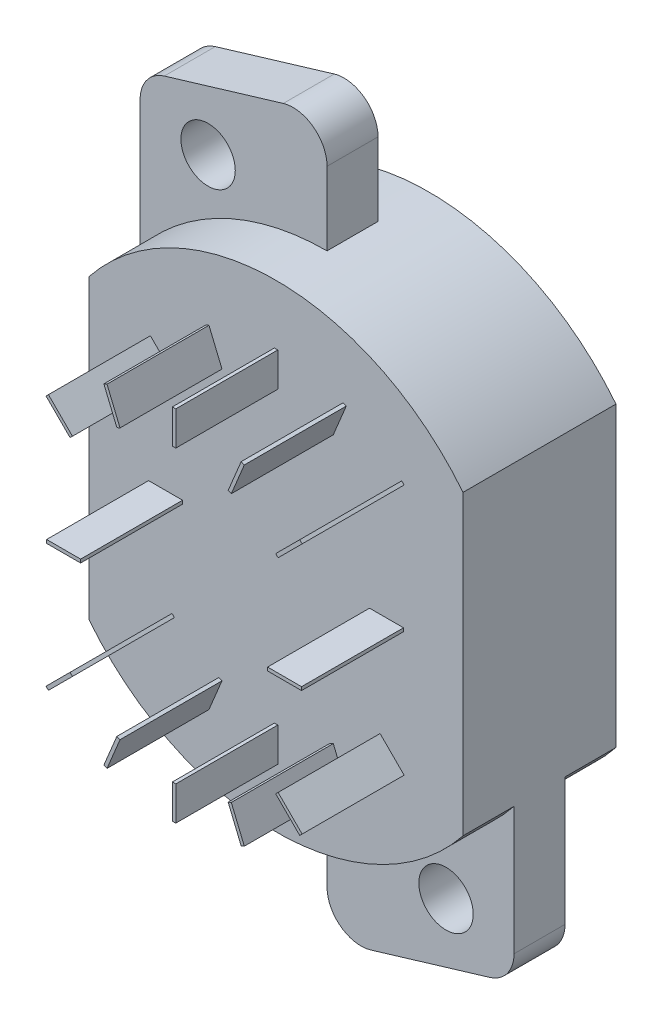
SolidWorks part; units mm, degrees
ref_plane "正面" through (0, 0, 0) normal (0, 0, 1) x (1, 0, 0)
ref_plane "平面" through (0, 0, 0) normal (0, 1, 0) x (1, 0, 0)
ref_plane "右側面" through (0, 0, 0) normal (1, 0, 0) x (0, 0, -1)
sketch "ｽｹｯﾁ1" plane through (0, 0, 0) normal (0, 0, 1) x (1, 0, 0)
  line L1 (-11, 8.75) -> (11, 8.75) construction
  line L2 (-11, 8.75) -> (-11, -8.75)
  line L3 (-11, -8.75) -> (11, -8.75) construction
  line L4 (11, 8.75) -> (11, -8.75)
  line L5 (-11, 8.75) -> (11, -8.75) construction
  line L6 (-11, -8.75) -> (11, 8.75) construction
  arc A0 (-11, 8.75) -> (11, 8.75) centre (0, 0) cw
  arc A1 (-11, -8.75) -> (11, -8.75) centre (0, 0) ccw
  point P0 (0, 0)
  dimension "D1" = 17.5
  dimension "D2" = 22
extrude "ﾎﾞｽ - 押し出し1" add sketch "ｽｹｯﾁ1" along normal blind 3
sketch "ｽｹｯﾁ2" plane through (0, 0, 3) normal (0, 0, 1) x (1, 0, 0)
  line L0 (-11, 8.75) -> (-11, 17.75)
  line L1 (-11, 17.75) -> (0, 21.0557)
  line L2 (0, 21.0557) -> (0, 14.0557)
  line L3 (11, -8.75) -> (11, -17.75)
  line L4 (11, -17.75) -> (0, -21.0557)
  line L5 (0, -21.0557) -> (0, -14.0557)
  line L8 (11, -8.75) -> (11, 8.75)
  line L9 (-11, 8.75) -> (-11, -8.75)
  line L10 (11, -8.75) -> (11, 8.75)
  line L11 (-11, 8.75) -> (-11, -8.75)
  arc A0 (11, 8.75) -> (-11, 8.75) centre (0, 0) ccw construction
  arc A1 (-11, -8.75) -> (11, -8.75) centre (0, 0) ccw construction
  arc A2 (0, -14.0557) -> (11, -8.75) centre (0, 0) ccw construction
  arc A3 (0, 14.0557) -> (-11, 8.75) centre (0, 0) ccw construction
  arc A4 (11, 8.75) -> (0, 14.0557) centre (0, 0) ccw construction
  arc A5 (-11, -8.75) -> (0, -14.0557) centre (0, 0) ccw construction
  arc A6 (0, -14.0557) -> (11, -8.75) centre (0, 0) ccw construction
  arc A7 (0, 14.0557) -> (-11, 8.75) centre (0, 0) ccw construction
  arc A8 (-11, -8.75) -> (11, -8.75) centre (0, 0) ccw
  arc A9 (11, 8.75) -> (-11, 8.75) centre (0, 0) ccw
  arc A10 (-11, -8.75) -> (0, -14.0557) centre (0, 0) ccw
  arc A11 (11, 8.75) -> (0, 14.0557) centre (0, 0) ccw
  dimension "D1" = 7
  dimension "D2" = 9
  dimension "D3" = 9
  dimension "D4" = 7
  dimension "D5" = 0
extrude "ﾎﾞｽ - 押し出し2" add sketch "ｽｹｯﾁ2" along normal blind 3
sketch "ｽｹｯﾁ3" plane through (0, 0, 6) normal (0, 0, 1) x (1, 0, 0)
  line L1 (-11, 8.75) -> (11, 8.75) construction
  line L2 (-11, 8.75) -> (-11, -8.75)
  line L3 (-11, -8.75) -> (11, -8.75) construction
  line L4 (11, 8.75) -> (11, -8.75)
  line L5 (-11, 8.75) -> (11, -8.75) construction
  line L6 (-11, -8.75) -> (11, 8.75) construction
  arc A0 (-11, 8.75) -> (11, 8.75) centre (0, 0) cw
  arc A1 (-11, -8.75) -> (11, -8.75) centre (0, 0) ccw
  point P0 (0, 0)
extrude "ﾎﾞｽ - 押し出し3" add sketch "ｽｹｯﾁ3" along normal blind 3
sketch "ｽｹｯﾁ4" plane through (0, 0, 6) normal (0, 0, 1) x (1, 0, 0)
  line L0 (-7, 18.9521) -> (-7, 12.1886) construction
  line L1 (0, 21.0557) -> (-11, 17.75) construction
  line L2 (7, -12.1886) -> (7, -18.9521) construction
  line L3 (0, -21.0557) -> (11, -17.75) construction
  line L4 (-11, 17.75) -> (-11, 8.75) construction
  line L5 (11, -17.75) -> (11, -8.75) construction
  arc A0 (11, 8.75) -> (-11, 8.75) centre (0, 0) ccw construction
  arc A1 (-11, -8.75) -> (11, -8.75) centre (0, 0) ccw construction
  circle A2 centre (-7, 15.4521) radius 1.6
  circle A3 centre (7, -15.4521) radius 1.6
  dimension "D3" = 3.2
  dimension "D4" = 3.5
  dimension "D5" = 3.2
  dimension "D1" = 4
  dimension "D2" = 4
  dimension "D6" = 3.5
extrude "ｶｯﾄ - 押し出し1" cut sketch "ｽｹｯﾁ4" against normal through all
fillet "ﾌｨﾚｯﾄ1" radius 2 4 edges at (11, -17.75, 4.5) (0, -21.0557, 4.5) (0, 21.0557, 4.5) (-11, 17.75, 4.5)
sketch "ｽｹｯﾁ5" plane through (0, 0, 9) normal (0, 0, 1) x (1, 0, 0)
  line L2 (3.9471, 9.7905) -> (3.1817, 7.9427)
  line L3 (-0.1, 10.5557) -> (0.1, 10.5557)
  line L4 (6.5, -7.0044) -> (6.5, 7.0044)
  line L5 (-6.5, 7.0044) -> (-6.5, -7.0044)
  line L6 (6.5, -7.0044) -> (6.5, 7.0044) construction
  line L7 (-6.5, 7.0044) -> (-6.5, -7.0044) construction
  line L8 (-0.1, 10.5557) -> (-0.1, 8.5557)
  line L9 (-0.1, 8.5557) -> (0.1, 8.5557)
  line L10 (0.1, 10.5557) -> (0.1, 8.5557)
  line L11 (-0.1, 10.5557) -> (0.1, 8.5557) construction
  line L12 (-0.1, 8.5557) -> (0.1, 10.5557) construction
  line L13 (3.9471, 9.7905) -> (4.1319, 9.7139)
  line L14 (4.1319, 9.7139) -> (3.3665, 7.8662)
  line L15 (3.1817, 7.9427) -> (3.3665, 7.8662)
  line L16 (7.3933, 7.5347) -> (5.9791, 6.1205)
  line L17 (7.3933, 7.5347) -> (7.5347, 7.3933)
  line L18 (7.5347, 7.3933) -> (6.1205, 5.9791)
  line L19 (5.9791, 6.1205) -> (6.1205, 5.9791)
  line L32 (7.5347, -7.3933) -> (6.1205, -5.9791)
  line L33 (7.5347, -7.3933) -> (7.3933, -7.5347)
  line L34 (7.3933, -7.5347) -> (5.9791, -6.1205)
  line L35 (6.1205, -5.9791) -> (5.9791, -6.1205)
  line L36 (4.1319, -9.7139) -> (3.3665, -7.8662)
  line L37 (4.1319, -9.7139) -> (3.9471, -9.7905)
  line L38 (3.9471, -9.7905) -> (3.1817, -7.9427)
  line L39 (3.3665, -7.8662) -> (3.1817, -7.9427)
  line L40 (0.1, -10.5557) -> (0.1, -8.5557)
  line L41 (0.1, -10.5557) -> (-0.1, -10.5557)
  line L42 (-0.1, -10.5557) -> (-0.1, -8.5557)
  line L43 (0.1, -8.5557) -> (-0.1, -8.5557)
  line L44 (-3.9471, -9.7905) -> (-3.1817, -7.9427)
  line L45 (-3.9471, -9.7905) -> (-4.1319, -9.7139)
  line L46 (-4.1319, -9.7139) -> (-3.3665, -7.8662)
  line L47 (-3.1817, -7.9427) -> (-3.3665, -7.8662)
  line L48 (-7.3933, -7.5347) -> (-5.9791, -6.1205)
  line L49 (-7.3933, -7.5347) -> (-7.5347, -7.3933)
  line L50 (-7.5347, -7.3933) -> (-6.1205, -5.9791)
  line L51 (-5.9791, -6.1205) -> (-6.1205, -5.9791)
  line L64 (-7.5347, 7.3933) -> (-6.1205, 5.9791)
  line L65 (-7.5347, 7.3933) -> (-7.3933, 7.5347)
  line L66 (-7.3933, 7.5347) -> (-5.9791, 6.1205)
  line L67 (-6.1205, 5.9791) -> (-5.9791, 6.1205)
  line L68 (-4.1319, 9.7139) -> (-3.3665, 7.8662)
  line L69 (-4.1319, 9.7139) -> (-3.9471, 9.7905)
  line L70 (-3.9471, 9.7905) -> (-3.1817, 7.9427)
  line L71 (-3.3665, 7.8662) -> (-3.1817, 7.9427)
  line L72 (9.7139, 4.1319) -> (7.8662, 3.3665) [skipped]
  line L73 (9.7139, 4.1319) -> (9.7905, 3.9471) [skipped]
  line L74 (9.7905, 3.9471) -> (7.9427, 3.1817) [skipped]
  line L75 (7.8662, 3.3665) -> (7.9427, 3.1817) [skipped]
  line L76 (10.5557, 0.1) -> (8.5557, 0.1) [skipped]
  line L77 (10.5557, 0.1) -> (10.5557, -0.1) [skipped]
  line L78 (10.5557, -0.1) -> (8.5557, -0.1) [skipped]
  line L79 (8.5557, 0.1) -> (8.5557, -0.1) [skipped]
  line L80 (9.7905, -3.9471) -> (7.9427, -3.1817) [skipped]
  line L81 (9.7905, -3.9471) -> (9.7139, -4.1319) [skipped]
  line L82 (9.7139, -4.1319) -> (7.8662, -3.3665) [skipped]
  line L83 (7.9427, -3.1817) -> (7.8662, -3.3665) [skipped]
  line L84 (-9.7139, -4.1319) -> (-7.8662, -3.3665) [skipped]
  line L85 (-9.7139, -4.1319) -> (-9.7905, -3.9471) [skipped]
  line L86 (-9.7905, -3.9471) -> (-7.9427, -3.1817) [skipped]
  line L87 (-7.8662, -3.3665) -> (-7.9427, -3.1817) [skipped]
  line L88 (-10.5557, -0.1) -> (-8.5557, -0.1) [skipped]
  line L89 (-10.5557, 0.1) -> (-8.5557, 0.1) [skipped]
  line L90 (-8.5557, -0.1) -> (-8.5557, 0.1) [skipped]
  line L91 (-9.7905, 3.9471) -> (-7.9427, 3.1817) [skipped]
  line L92 (-9.7905, 3.9471) -> (-9.7139, 4.1319) [skipped]
  line L93 (-9.7139, 4.1319) -> (-7.8662, 3.3665) [skipped]
  line L94 (-7.9427, 3.1817) -> (-7.8662, 3.3665) [skipped]
  line L96 (-7.5, 0.1) -> (-5.5, 0.1)
  line L97 (-7.5, 0.1) -> (-7.5, -0.1)
  line L98 (-7.5, -0.1) -> (-5.5, -0.1)
  line L99 (-5.5, 0.1) -> (-5.5, -0.1)
  line L100 (-7.5, 0.1) -> (-5.5, -0.1) construction
  line L101 (-7.5, -0.1) -> (-5.5, 0.1) construction
  line L102 (5.5, 0.1) -> (7.5, 0.1)
  line L103 (5.5, 0.1) -> (5.5, -0.1)
  line L104 (5.5, -0.1) -> (7.5, -0.1)
  line L105 (7.5, 0.1) -> (7.5, -0.1)
  line L106 (5.5, 0.1) -> (7.5, -0.1) construction
  line L107 (5.5, -0.1) -> (7.5, 0.1) construction
  line L108 (-10.5557, -0.1) -> (-10.5557, 0.1) [skipped]
  arc A4 (-6.5, -7.0044) -> (6.5, -7.0044) centre (0, 0) ccw
  arc A5 (6.5, 7.0044) -> (-6.5, 7.0044) centre (0, 0) ccw
  arc A6 (-6.5, -7.0044) -> (6.5, -7.0044) centre (0, 0) ccw construction
  arc A7 (6.5, 7.0044) -> (-6.5, 7.0044) centre (0, 0) ccw construction
  point P0 (0, 9.5557)
  point P5 (-6.5, 0)
  point P24 (6.5, 0)
  point P74 (0, 0)
  dimension "D2" = 0.2
  dimension "D3" = 2
  dimension "D5" = 2
  dimension "D6" = 0.2
  dimension "D7" = 0.2
  dimension "D8" = 2
  dimension "D1" = 4.5
  dimension "D4" = 16
extrude "ﾎﾞｽ - 押し出し4" add sketch "ｽｹｯﾁ5" along normal blind 6
